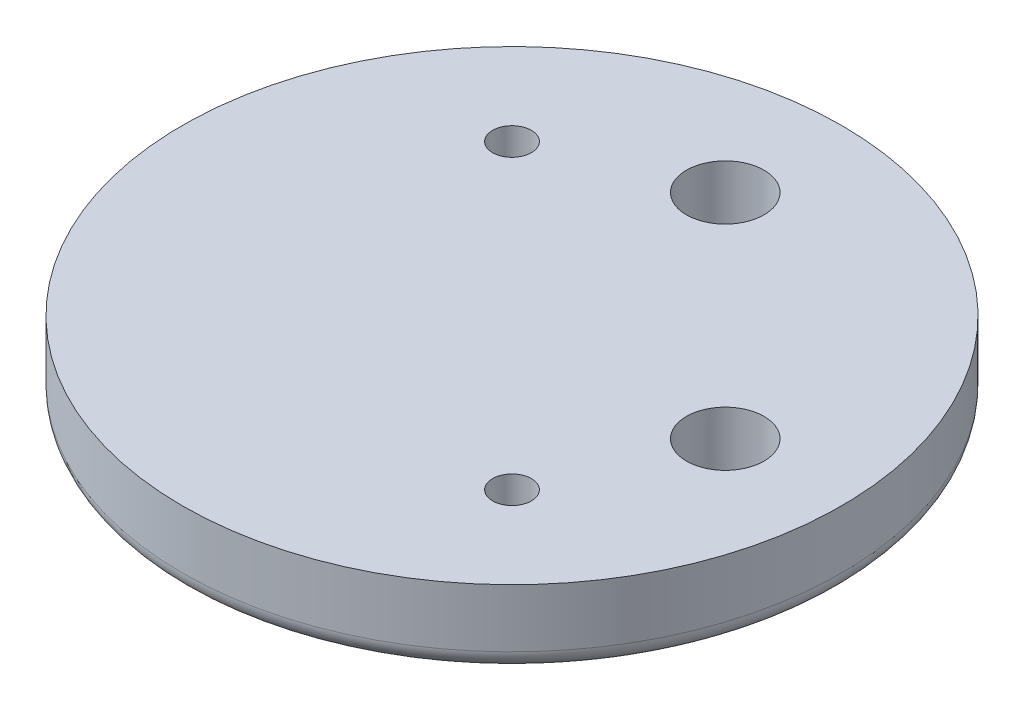
SolidWorks part; units mm, degrees
ref_plane "前视基准面" through (0, 0, 0) normal (0, 0, 1) x (1, 0, 0)
ref_plane "上视基准面" through (0, 0, 0) normal (0, 1, 0) x (1, 0, 0)
ref_plane "右视基准面" through (0, 0, 0) normal (1, 0, 0) x (0, 0, -1)
other "Configuration Table"
sketch "草图1" plane through (0, 0, 0) normal (0, 1, 0) x (1, 0, 0)
  circle A0 centre (0, 0) radius 17
  dimension "D1" = 34
extrude "凸台-拉伸1" add sketch "草图1" along normal blind 4
sketch "草图2" plane through (0, 0, 0) normal (0, 1, 0) x (1, 0, 0)
  line L0 (0, 4.5) -> (0, -4.5) construction
  line L1 (2.5, 4.5) -> (2.5, -4.5)
  line L2 (-2.5, 4.5) -> (-2.5, -4.5)
  arc A0 (2.5, 4.5) -> (-2.5, 4.5) centre (0, 4.5) ccw
  arc A1 (-2.5, -4.5) -> (2.5, -4.5) centre (0, -4.5) ccw
  point P2 (0, 0)
  point P8 (0, 7)
  point P9 (0, -7)
  dimension "D1" = 14
  dimension "D2" = 5
extrude "切除-拉伸1" cut sketch "草图2" along normal blind 2
sketch "草图3" plane through (0, 4, 0) normal (0, 1, 0) x (1, 0, 0)
  line L0 (-7.7782, 7.7782) -> (0, 0) construction
  line L1 (0, 0) -> (0, 11) construction
  line L2 (0, 0) -> (12.0208, 12.0208) construction
  circle A0 centre (0, 0) radius 11 construction
  circle A1 centre (0, 11) radius 2
  circle A2 centre (-7.7782, 7.7782) radius 1
  circle A3 centre (0, 0) radius 17 construction
  circle A4 centre (11, 0) radius 2
  circle A5 centre (7.7782, -7.7782) radius 1
  dimension "D1" = 22
  dimension "D2" = 4
  dimension "D3" = 2
  dimension "D4" = 45
  dimension "D5" = 45
extrude "切除-拉伸2" cut sketch "草图3" against normal up to next
fillet "圆角1" radius 1 1 edges at (0, 0, 17)
